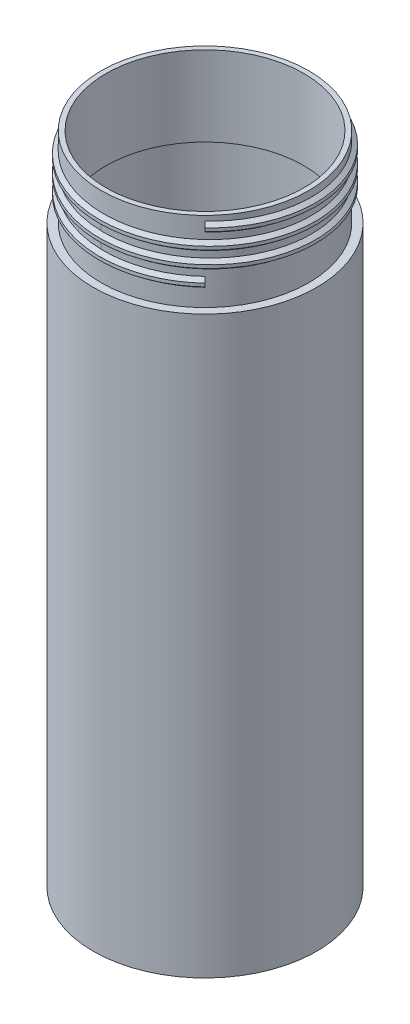
SolidWorks part; units mm, degrees
material "AISI 304"
ref_plane "Front Plane" through (0, 0, 0) normal (0, 0, 1) x (1, 0, 0)
ref_plane "Top Plane" through (0, 0, 0) normal (0, 1, 0) x (1, 0, 0)
ref_plane "Right Plane" through (0, 0, 0) normal (1, 0, 0) x (0, 0, -1)
sketch "Sketch1" plane through (0, 0, 0) normal (0, 1, 0) x (1, 0, 0)
  circle A0 centre (0, 0) radius 35
  dimension "D1" = 70
extrude "Boss-Extrude1" add sketch "Sketch1" along normal blind 180
ref_plane "Plane1" through (0, 180, 0) normal (0, 1, 0) x (1, 0, 0)
sketch "Sketch8" plane through (0, 180, 0) normal (0, 1, 0) x (1, 0, 0)
  circle A0 centre (0, 0) radius 32.5
  circle A1 centre (0, 0) radius 35 construction
  dimension "D1" = 2.5
extrude "Cut-Extrude2" cut sketch "Sketch8" against normal blind 164
ref_plane "Plane3" through (0, 0, 0) normal (0, -1, 0) x (-1, 0, 0)
sketch "Sketch9" plane through (0, 0, 0) normal (0, -1, 0) x (-1, 0, 0)
  circle A0 centre (0, 0) radius 33
  circle A1 centre (0, 0) radius 35 construction
  dimension "D1" = 2
extrude "Cut-Extrude3" cut sketch "Sketch9" against normal blind 15
ref_plane "Plane4" through (0, 12, 0) normal (0, -1, 0) x (-1, 0, 0)
sketch "Sketch19" plane through (0, 12, 0) normal (0, -1, 0) x (-1, 0, 0)
  circle A0 centre (0, 0) radius 33 construction
  circle A1 centre (0, 0) radius 33
curve "Helix/Spiral2" pitch 3 height 9 turns 3
ref_plane "Plane6" through (23.3345, 3, -23.3345) normal (-0.707, -0.0145, -0.707) x (-0.7069, -0.0145, 0.7072)
sketch "Sketch20" plane through (23.3345, 3, -23.3345) normal (-0.707, -0.0145, -0.707) x (-0.7069, -0.0145, 0.7072)
  line L0 (-0.3, 1) -> (-0.3, -1)
  line L1 (-0.3, 0) -> (0.7, 0) construction
  line L2 (0.7, 0.25) -> (0.7, -0.25)
  line L3 (-0.3, -1) -> (0.7, -0.25)
  line L4 (0.7, 0.25) -> (-0.3, 1)
  point P3 (-0.3, 0)
  point P7 (0, 0)
  point P8 (0.7, 0)
  dimension "D1" = 2
  dimension "D2" = 0.5
  dimension "D3" = 1
  dimension "D4" = 0.3
sweep "Sweep2" add profiles "Sketch20" path "Helix/Spiral2"
sketch "Sketch21" plane through (0, 180, 0) normal (0, 1, 0) x (1, 0, 0)
  circle A0 centre (0, 0) radius 32.5
  circle A3 centre (0, 0) radius 32.5 construction
extrude "Boss-Extrude3" add sketch "Sketch21" along normal blind 25 separate body
ref_plane "Plane7" through (0, 205, 0) normal (0, 1, 0) x (1, 0, 0)
sketch "Sketch22" plane through (0, 205, 0) normal (0, 1, 0) x (1, 0, 0)
  circle A0 centre (0, 0) radius 31
  circle A1 centre (0, 0) radius 32.5 construction
  dimension "D1" = 1.5
extrude "Cut-Extrude4" cut sketch "Sketch22" against normal blind 103
ref_plane "Plane8" through (0, 187, 0) normal (0, 1, 0) x (1, 0, 0)
sketch "Sketch23" plane through (0, 187, 0) normal (0, 1, 0) x (1, 0, 0)
  circle A0 centre (0, 0) radius 32.5 construction
  circle A1 centre (0, 0) radius 32.5
curve "Helix/Spiral3" pitch 5 height 15 turns 3
ref_plane "Plane9" through (22.981, 187, 22.981) normal (-0.7069, 0.0245, 0.7069) x (0.7073, 0.0241, 0.7065)
sketch "Sketch24" plane through (22.981, 187, 22.981) normal (-0.7069, 0.0245, 0.7069) x (0.7073, 0.0241, 0.7065)
  line L0 (-0.7, 2) -> (-0.7, -2)
  line L1 (1.3, 0.5) -> (1.3, -0.5)
  line L2 (-0.7, 0) -> (1.3, 0) construction
  line L3 (-0.7, 2) -> (1.3, 0.5)
  line L4 (-0.7, -2) -> (1.3, -0.5)
  point P3 (-0.7, 0)
  point P6 (1.3, 0)
  point P10 (0, 0)
  dimension "D1" = 1
  dimension "D2" = 4
  dimension "D3" = 2
  dimension "D4" = 0.7
sweep "Sweep3" add profiles "Sketch24" path "Helix/Spiral3"
ref_plane "Plane10" through (0, 180, 0) normal (0, 1, 0) x (1, 0, 0)
sketch "Sketch25" plane through (0, 180, 0) normal (0, 1, 0) x (1, 0, 0)
  line L0 (-34.3616, 0.9804) -> (-34.2914, -2.4608) construction
  line L1 (-34.0543, 0.9867) -> (-33.9841, -2.4545)
  line L2 (-34.6689, 0.9742) -> (-34.5987, -2.4671)
  line L3 (-34.3757, 1.6707) -> (-34.2774, -3.1472) construction
  arc A0 (-34.0543, 0.9867) -> (-34.6689, 0.9742) centre (-34.3616, 0.9804) ccw
  arc A1 (-34.5987, -2.4671) -> (-33.9841, -2.4545) centre (-34.2914, -2.4608) ccw
  point P2 (-34.3265, -0.7402)
extrude "Cut-Extrude5" cut sketch "Sketch25" against normal blind 1
ref_plane "Plane11" through (0, 179, 0) normal (0, 1, 0) x (1, 0, 0)
sketch "Sketch26" plane through (0, 179, 0) normal (0, 1, 0) x (1, 0, 0)
  line L0 (-34.3399, -0.085) -> (-34.3131, -1.3957) construction
  line L1 (-34.1572, -0.0812) -> (-34.1304, -1.3919)
  line L2 (-34.5226, -0.0887) -> (-34.4958, -1.3994)
  line L3 (-34.6689, 0.9742) -> (-34.5987, -2.4671) construction
  line L4 (-33.9841, -2.4545) -> (-34.0543, 0.9867) construction
  line L5 (-34.3616, 0.9804) -> (-34.2914, -2.4608) construction
  arc A0 (-34.1572, -0.0812) -> (-34.5226, -0.0887) centre (-34.3399, -0.085) ccw
  arc A1 (-34.4958, -1.3994) -> (-34.1304, -1.3919) centre (-34.3131, -1.3957) ccw
  arc A5 (-34.0543, 0.9867) -> (-34.6689, 0.9742) centre (-34.3616, 0.9804) ccw construction
  arc A6 (-34.5987, -2.4671) -> (-33.9841, -2.4545) centre (-34.2914, -2.4608) ccw construction
  point P2 (-34.3265, -0.7403)
  point P11 (-34.3436, 0.0977)
  point P17 (-34.3679, 1.2877)
  point P18 (-34.2851, -2.7681)
  point P22 (-34.3094, -1.5783)
  dimension "D1" = 1.19
  dimension "D2" = 1.19
extrude "Cut-Extrude6" cut sketch "Sketch26" against normal through all
ref_plane "Plane12" through (0, 0, 0) normal (0, -1, 0) x (-1, 0, 0)
sketch "Sketch30" plane through (0, 0, 0) normal (0, -1, 0) x (-1, 0, 0)
  line L0 (34.2914, -2.4608) -> (34.3616, 0.9804) construction
  line L1 (33.9841, -2.4545) -> (34.0543, 0.9867)
  line L2 (34.5987, -2.4671) -> (34.6689, 0.9742)
  line L3 (33.9841, -2.4545) -> (34.0543, 0.9867) construction
  arc A0 (33.9841, -2.4545) -> (34.5987, -2.4671) centre (34.2914, -2.4608) ccw
  arc A1 (34.6689, 0.9742) -> (34.0543, 0.9867) centre (34.3616, 0.9804) ccw
  arc A2 (34.6689, 0.9742) -> (34.0543, 0.9867) centre (34.3616, 0.9804) ccw construction
  arc A3 (33.9841, -2.4545) -> (34.5987, -2.4671) centre (34.2914, -2.4608) ccw construction
  point P2 (34.3265, -0.7402)
extrude "Cut-Extrude7" cut sketch "Sketch30" against normal blind 1 contours L2 A1 L1 A0
